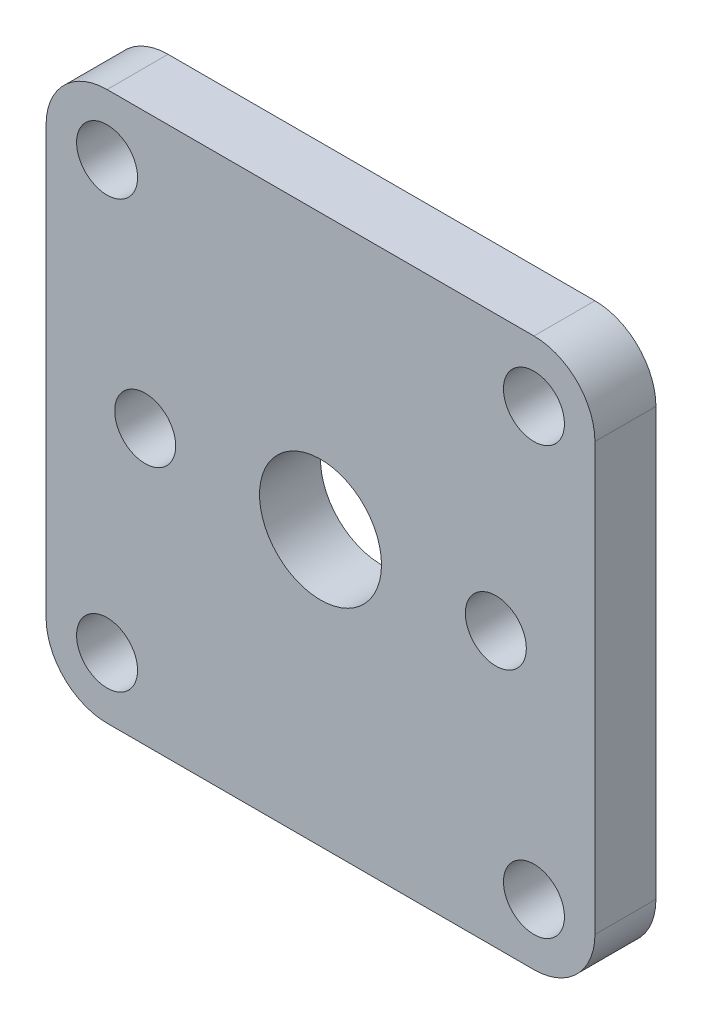
SolidWorks part; units mm, degrees
material "Thornel Mat VMA"
ref_plane "前视基准面" through (0, 0, 0) normal (0, 0, 1) x (1, 0, 0)
ref_plane "上视基准面" through (0, 0, 0) normal (0, 1, 0) x (1, 0, 0)
ref_plane "右视基准面" through (0, 0, 0) normal (1, 0, 0) x (0, 0, -1)
sketch "草图1" plane through (0, 0, 0) normal (0, 0, 1) x (1, 0, 0)
  line L1 (-9, 9) -> (9, 9)
  line L2 (-9, 9) -> (-9, -9)
  line L3 (-9, -9) -> (9, -9)
  line L4 (9, 9) -> (9, -9)
  line L5 (-9, 9) -> (9, -9) construction
  line L6 (-9, -9) -> (9, 9) construction
  circle A0 centre (0, 0) radius 2
  point P0 (0, 0)
  dimension "D2" = 4
  dimension "D1" = 18
extrude "凸台-拉伸1" add sketch "草图1" along normal blind 2
sketch "草图2" plane through (0, 0, 2) normal (0, 0, 1) x (1, 0, 0)
  line L1 (-7, 7) -> (7, 7) construction
  line L2 (-7, 7) -> (-7, -7) construction
  line L3 (-7, -7) -> (7, -7) construction
  line L4 (7, 7) -> (7, -7) construction
  line L5 (-7, 7) -> (7, -7) construction
  line L6 (-7, -7) -> (7, 7) construction
  point P0 (0, 0)
  dimension "D1" = 14
hole_wizard "大小mm 暗销孔1" positions "3D草图1" profile "草图3" hole size "Ø2.0" standard "GB" end condition through all
sketch3d "3D草图1"
  point P0 (-7, 7, 2)
  point P3 (7, 7, 2)
  point P6 (7, -7, 2)
  point P9 (-7, -7, 2)
sketch "草图3" plane through (-7, 7, 2) normal (1, 0, 0) x (0, -1, 0)
  line L0 (0, 0) -> (0, 2)
  line L1 (0, 2) -> (1, 2)
  line L2 (1, 2) -> (1, 0)
  line L5 (1, 0) -> (0, 0)
  line L11 (0, -6.35) -> (0, 107.95) construction
  dimension "通孔孔直径" = 2
  dimension "通孔孔深度" = 2
fillet "圆角1" radius 2 4 edges at (-9, 9, 1) (-9, -9, 1) (9, -9, 1) (9, 9, 1)
sketch "草图4" plane through (0, 0, 2) normal (0, 0, 1) x (1, 0, 0)
  line L0 (-5.75, 0) -> (5.75, 0) construction
  point P5 (0, 0)
  dimension "D1" = 11.5
hole_wizard "大小mm 暗销孔2" positions "3D草图2" profile "草图5" hole size "Ø2.0" standard "GB" end condition through all
sketch3d "3D草图2"
  point P0 (-5.75, 0, 2)
  point P3 (5.75, 0, 2)
sketch "草图5" plane through (-5.75, 0, 2) normal (1, 0, 0) x (0, -1, 0)
  line L0 (0, 0) -> (0, 2)
  line L1 (0, 2) -> (1, 2)
  line L2 (1, 2) -> (1, 0)
  line L5 (1, 0) -> (0, 0)
  line L11 (0, -6.35) -> (0, 107.95) construction
  dimension "通孔孔直径" = 2
  dimension "通孔孔深度" = 2
